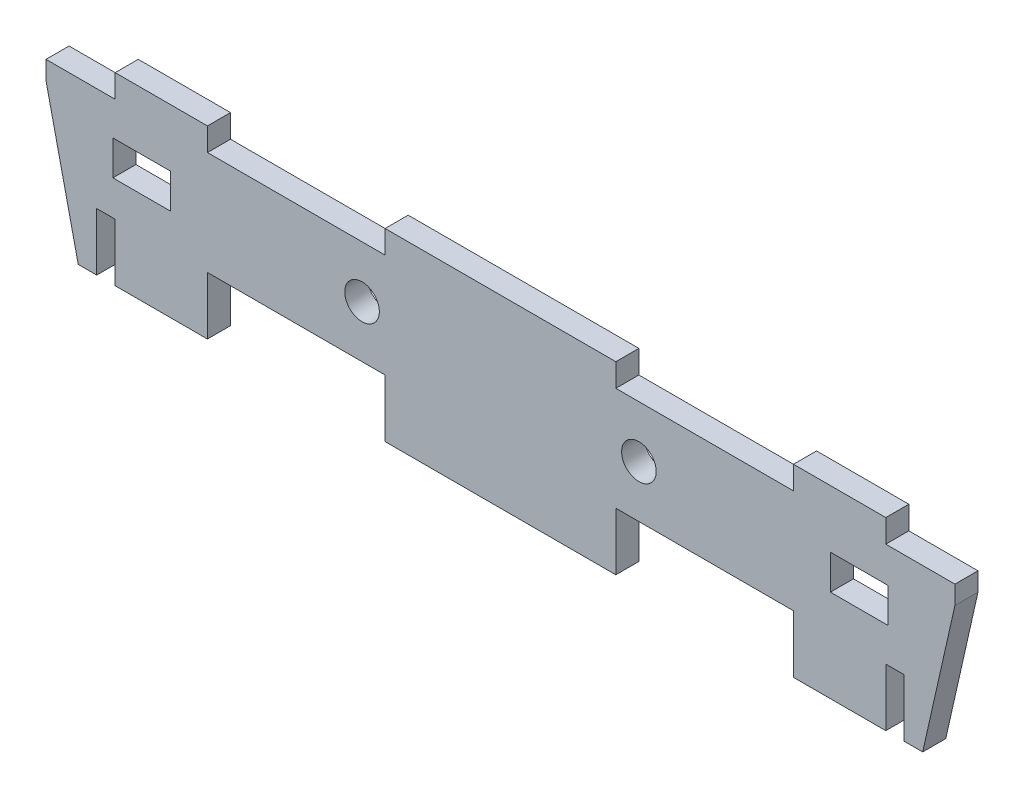
SolidWorks part; units mm, degrees
ref_plane "Front Plane" through (0, 0, 0) normal (0, 0, 1) x (1, 0, 0)
ref_plane "Top Plane" through (0, 0, 0) normal (0, 1, 0) x (1, 0, 0)
ref_plane "Right Plane" through (0, 0, 0) normal (1, 0, 0) x (0, 0, -1)
sketch "Sketch1" plane through (0, 0, 0) normal (0, 0, 1) x (1, 0, 0)
  line L0 (33.4, -27.6) -> (33.4, -32.6) construction
  line L2 (25.4, -27.6) -> (25.4, -32.6) construction
  line L3 (28.6, -24.6) -> (33.6, -24.6) construction
  line L4 (28.6, -21.6) -> (33.6, -21.6) construction
  line L5 (33.4, -16.6) -> (33.4, -18.6) construction
  line L6 (25.4, -16.6) -> (33.4, -16.6) construction
  line L7 (25.4, -16.6) -> (25.4, -18.6) construction
  line L8 (10, -16.6) -> (10, -18.6) construction
  line L9 (10, -16.6) -> (-10, -16.6) construction
  line L10 (-10, -16.6) -> (-10, -18.6) construction
  line L11 (-25.4, -16.6) -> (-25.4, -18.6) construction
  line L12 (-33.4, -16.6) -> (-25.4, -16.6) construction
  line L13 (-33.4, -16.6) -> (-33.4, -18.6) construction
  line L14 (10, -27.6) -> (10, -32.6) construction
  line L16 (-10, -27.6) -> (-10, -32.6) construction
  line L17 (-25.4, -27.6) -> (-25.4, -32.6) construction
  line L18 (-33.4, -32.6) -> (-25.4, -32.6) construction
  line L19 (-33.4, -27.6) -> (-33.4, -32.6) construction
  line L20 (-35, -32.6) -> (-35, -27.6) construction
  line L21 (35, -32.6) -> (35, -27.6) construction
  line L22 (39.3947, -18.6) -> (39.3947, -16.6) construction
  line L23 (-39.3947, -18.6) -> (-39.3947, -16.6) construction
  line L24 (33.4, -27.6) -> (33.4, -32.6)
  line L25 (-35, -32.6) -> (-36.6, -32.6)
  line L26 (25.4, -27.6) -> (25.4, -32.6)
  line L27 (28.6, -24.6) -> (33.6, -24.6)
  line L28 (28.6, -21.6) -> (33.6, -21.6)
  line L29 (33.4, -16.6) -> (33.4, -18.6)
  line L30 (25.4, -16.6) -> (33.4, -16.6)
  line L31 (25.4, -16.6) -> (25.4, -18.6)
  line L32 (10, -16.6) -> (10, -18.6)
  line L33 (10, -16.6) -> (-10, -16.6)
  line L34 (-10, -16.6) -> (-10, -18.6)
  line L35 (-25.4, -16.6) -> (-25.4, -18.6)
  line L36 (-33.4, -16.6) -> (-25.4, -16.6)
  line L37 (-33.4, -16.6) -> (-33.4, -18.6)
  line L38 (10, -27.6) -> (10, -32.6)
  line L39 (-36.6, -32.6) -> (-39.3947, -20.2)
  line L40 (-10, -27.6) -> (-10, -32.6)
  line L41 (-25.4, -27.6) -> (-25.4, -32.6)
  line L42 (-33.4, -32.6) -> (-25.4, -32.6)
  line L43 (-33.4, -27.6) -> (-33.4, -32.6)
  line L44 (-35, -32.6) -> (-35, -27.6)
  line L45 (35, -32.6) -> (35, -27.6)
  line L46 (39.3947, -18.6) -> (39.3947, -16.6) construction
  line L47 (-39.3947, -18.6) -> (-39.3947, -16.6) construction
  line L48 (25.4, -18.6) -> (10, -18.6)
  line L49 (-10, -18.6) -> (-25.4, -18.6)
  line L50 (-25.4, -27.6) -> (-10, -27.6)
  line L51 (-10, -32.6) -> (10, -32.6)
  line L52 (10, -27.6) -> (25.4, -27.6)
  line L53 (25.4, -32.6) -> (33.4, -32.6)
  line L54 (-39.3947, -20.2) -> (-39.3947, -18.6)
  line L55 (-33.4, -18.6) -> (-39.3947, -18.6)
  line L56 (-33.4, -27.6) -> (-35, -27.6)
  line L57 (33.4, -27.6) -> (35, -27.6)
  line L58 (35, -32.6) -> (36.6, -32.6)
  line L59 (36.6, -32.6) -> (39.3947, -20.2)
  line L60 (39.3947, -20.2) -> (39.3947, -18.6)
  line L61 (33.4, -18.6) -> (39.3947, -18.6)
  line L62 (33.6, -24.6) -> (33.6, -21.6)
  line L63 (28.6, -24.6) -> (28.6, -21.6)
  line L64 (-33.6, -24.6) -> (-28.6, -24.6) construction
  line L65 (-33.6, -21.6) -> (-28.6, -21.6) construction
  line L66 (-33.6, -24.6) -> (-28.6, -24.6)
  line L67 (-33.6, -21.6) -> (-28.6, -21.6)
  line L68 (-28.6, -24.6) -> (-28.6, -21.6)
  line L69 (-33.6, -24.6) -> (-33.6, -21.6)
extrude "Boss-Extrude1" add sketch "Sketch1" along normal blind 2
sketch "Sketch2" plane through (0, 0, 2) normal (0, 0, 1) x (1, 0, 0)
  line L0 (0, -32.6) -> (0, -16.6) construction
  line L1 (-10, -32.6) -> (10, -32.6) construction
  line L2 (10, -16.6) -> (-10, -16.6) construction
  line L3 (12, -23.1) -> (-12, -23.1) construction
  line L5 (10, -27.6) -> (25.4, -27.6) construction
  line L6 (25.4, -18.6) -> (10, -18.6) construction
  circle A0 centre (12, -23.1) radius 1.5
  circle A1 centre (-12, -23.1) radius 1.5
  point P8 (0, -23.1)
  dimension "D1" = 3
  dimension "D2" = 24
extrude "Cut-Extrude1" cut sketch "Sketch2" against normal up to next
